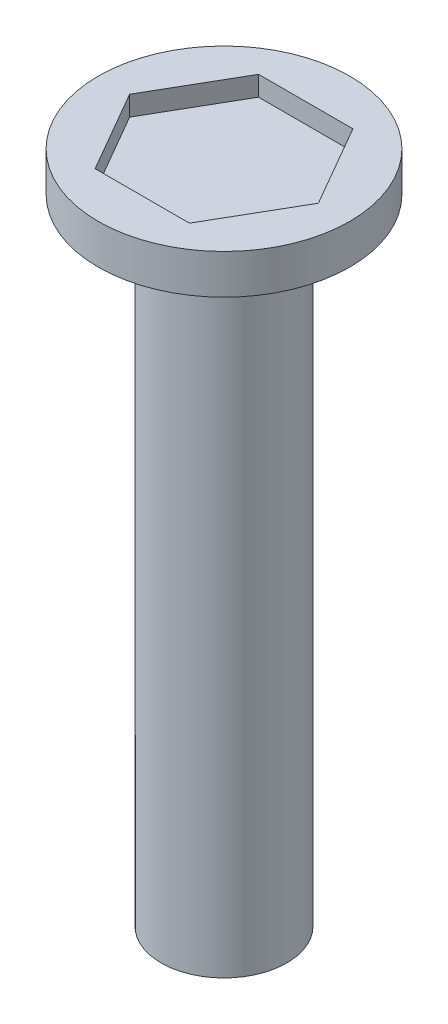
SolidWorks part; units mm, degrees
material "1060 Alloy"
ref_plane "Front Plane" through (0, 0, 0) normal (0, 0, 1) x (1, 0, 0)
ref_plane "Top Plane" through (0, 0, 0) normal (0, 1, 0) x (1, 0, 0)
ref_plane "Right Plane" through (0, 0, 0) normal (1, 0, 0) x (0, 0, -1)
sketch "Sketch1" plane through (0, 0, 0) normal (0, 0, 1) x (1, 0, 0)
  line L0 (0, 0) -> (3.175, 0)
  line L1 (3.175, 0) -> (3.175, -17)
  line L2 (3.175, -17) -> (1.5875, -17)
  line L3 (1.5875, -17) -> (1.5875, -1)
  line L4 (1.5875, -1) -> (0, -1)
  line L5 (0, -1) -> (0, 0)
  dimension "D1" = 1.5875
  dimension "D2" = 16
  dimension "D3" = 1
  dimension "D4" = 3.175
revolve "Revolve1" add sketch "Sketch1" angle 360 about L1
sketch "Sketch2" plane through (0, 0, 0) normal (0, 1, 0) x (1, 0, 0)
  line L1 (5.5562, 0) -> (4.3656, 2.0622)
  line L2 (4.3656, 2.0622) -> (1.9844, 2.0622)
  line L3 (1.9844, 2.0622) -> (0.7937, 0)
  line L4 (0.7937, 0) -> (1.9844, -2.0622)
  line L5 (1.9844, -2.0622) -> (4.3656, -2.0622)
  line L6 (4.3656, -2.0622) -> (5.5562, 0)
  circle A0 centre (3.175, 0) radius 3.175 construction
  circle A1 centre (3.175, 0) radius 2.3813 construction
  point P0 (3.175, 3.175)
  point P1 (0, 0)
extrude "Cut-Extrude1" cut sketch "Sketch2" against normal blind 0.5
